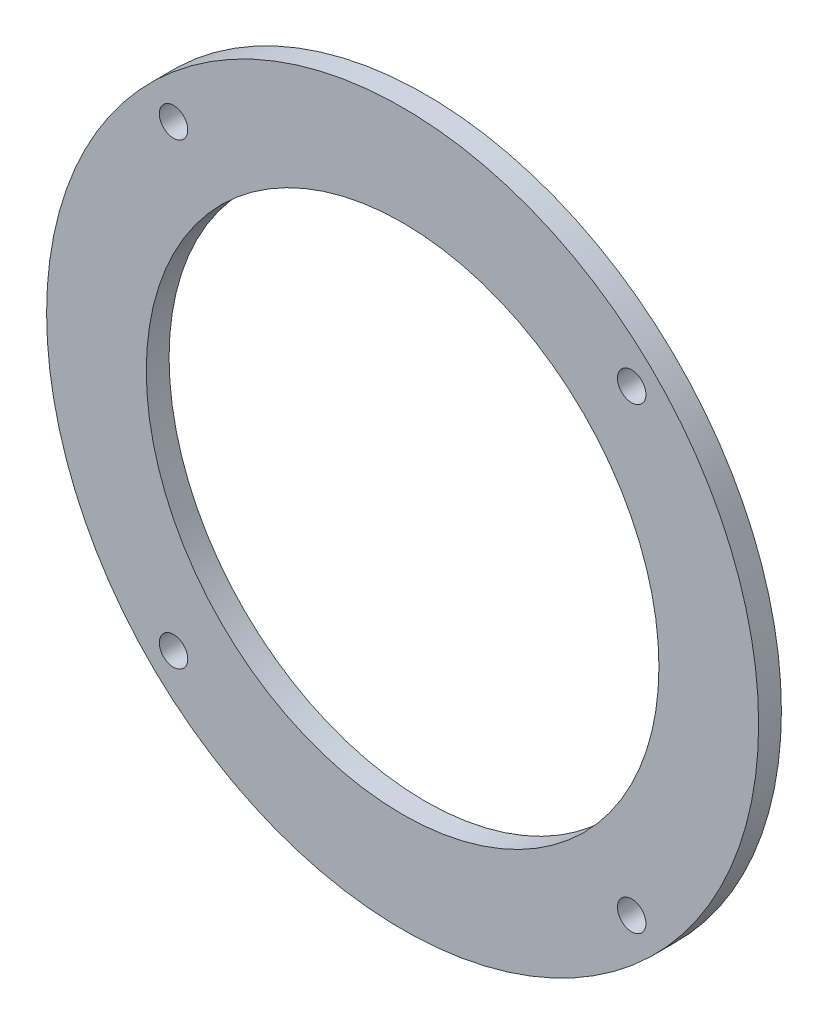
SolidWorks part; units mm, degrees
ref_plane "Front Plane" through (0, 0, 0) normal (0, 0, 1) x (1, 0, 0)
ref_plane "Top Plane" through (0, 0, 0) normal (0, 1, 0) x (1, 0, 0)
ref_plane "Right Plane" through (0, 0, 0) normal (1, 0, 0) x (0, 0, -1)
sketch "Sketch1" plane through (0, 0, 0) normal (0, 0, 1) x (1, 0, 0)
  line L0 (25, 0) -> (-25, 0) construction
  line L1 (0, -25) -> (0, 25) construction
  line L6 (0, 0) -> (-17.6777, -17.6777) construction
  line L8 (0, 0) -> (17.6777, 17.6777) construction
  line L10 (-17.6777, 17.6777) -> (17.6777, -17.6777) construction
  circle A1 centre (0, 0) radius 18
  circle A4 centre (0, 0) radius 25
  circle A5 centre (16.0867, -16.0867) radius 1
  circle A6 centre (-16.0867, -16.0867) radius 1
  circle A7 centre (-16.0867, 16.0867) radius 1
  circle A8 centre (16.0867, 16.0867) radius 1
  circle A9 centre (0, 0) radius 22.75 construction
extrude "Boss-Extrude2" add sketch "Sketch1" along normal blind 1.6 contours A5 | A6 | A1 | A4 | A7 | A8
sketch "Sketch2" plane through (0, 0, 0) normal (0, 0, 1) x (1, 0, 0)
  line L0 (0, 25) -> (0, -25) construction
  line L1 (25, 0) -> (-25, 0) construction
  line L2 (0, 25) -> (0, 23.8) construction
  line L3 (-0.7, 23.8) -> (0.7, 23.8) construction
  line L7 (4.5, 23.8) -> (4.5, 21.5) construction
  line L16 (0.7, 23.8) -> (1.9, 23.8)
  line L17 (0.7, 23.8) -> (0.7, 21.5)
  line L18 (0.7, 21.5) -> (1.9, 21.5)
  line L19 (1.9, 23.8) -> (1.9, 21.5)
  line L20 (3.3, 23.8) -> (4.5, 23.8)
  line L21 (3.3, 23.8) -> (3.3, 21.5)
  line L22 (3.3, 21.5) -> (4.5, 21.5)
  line L23 (4.5, 23.8) -> (4.5, 21.5)
  line L24 (1.9, 23.8) -> (3.3, 23.8) construction
  line L33 (-1.9, 23.8) -> (-3.3, 23.8) construction
  line L34 (-4.5, 23.8) -> (-4.5, 21.5) construction
  line L35 (-4.5, 23.8) -> (-4.5, 21.5)
  line L36 (-3.3, 21.5) -> (-4.5, 21.5)
  line L37 (-3.3, 23.8) -> (-3.3, 21.5)
  line L38 (-3.3, 23.8) -> (-4.5, 23.8)
  line L39 (-1.9, 23.8) -> (-1.9, 21.5)
  line L40 (-0.7, 21.5) -> (-1.9, 21.5)
  line L41 (-0.7, 23.8) -> (-0.7, 21.5)
  line L42 (-0.7, 23.8) -> (-1.9, 23.8)
  circle A0 centre (0, 0) radius 25 construction
  point P2 (0, 0)
extrude "Boss-Extrude3" add sketch "Sketch2" against normal blind 0.1
